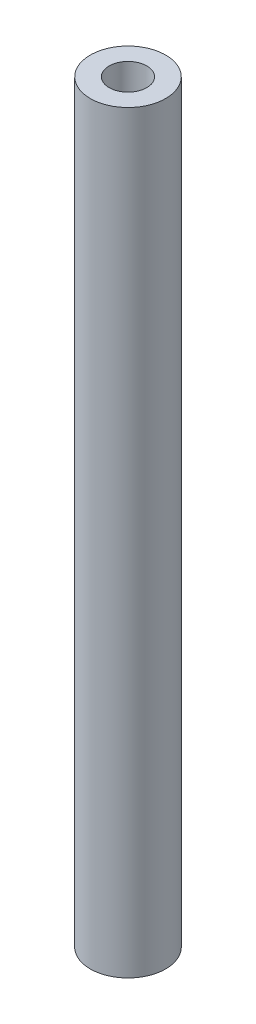
SolidWorks part; units mm, degrees
ref_plane "前视基准面" through (0, 0, 0) normal (0, 0, 1) x (1, 0, 0)
ref_plane "上视基准面" through (0, 0, 0) normal (0, 1, 0) x (1, 0, 0)
ref_plane "右视基准面" through (0, 0, 0) normal (1, 0, 0) x (0, 0, -1)
sketch "草图1" plane through (0, 0, 0) normal (0, 1, 0) x (1, 0, 0)
  circle A0 centre (0, 0) radius 3
  circle A1 centre (0, 0) radius 6
  dimension "D1" = 6
  dimension "D2" = 12
extrude "凸台-拉伸1" add sketch "草图1" along normal blind 120
